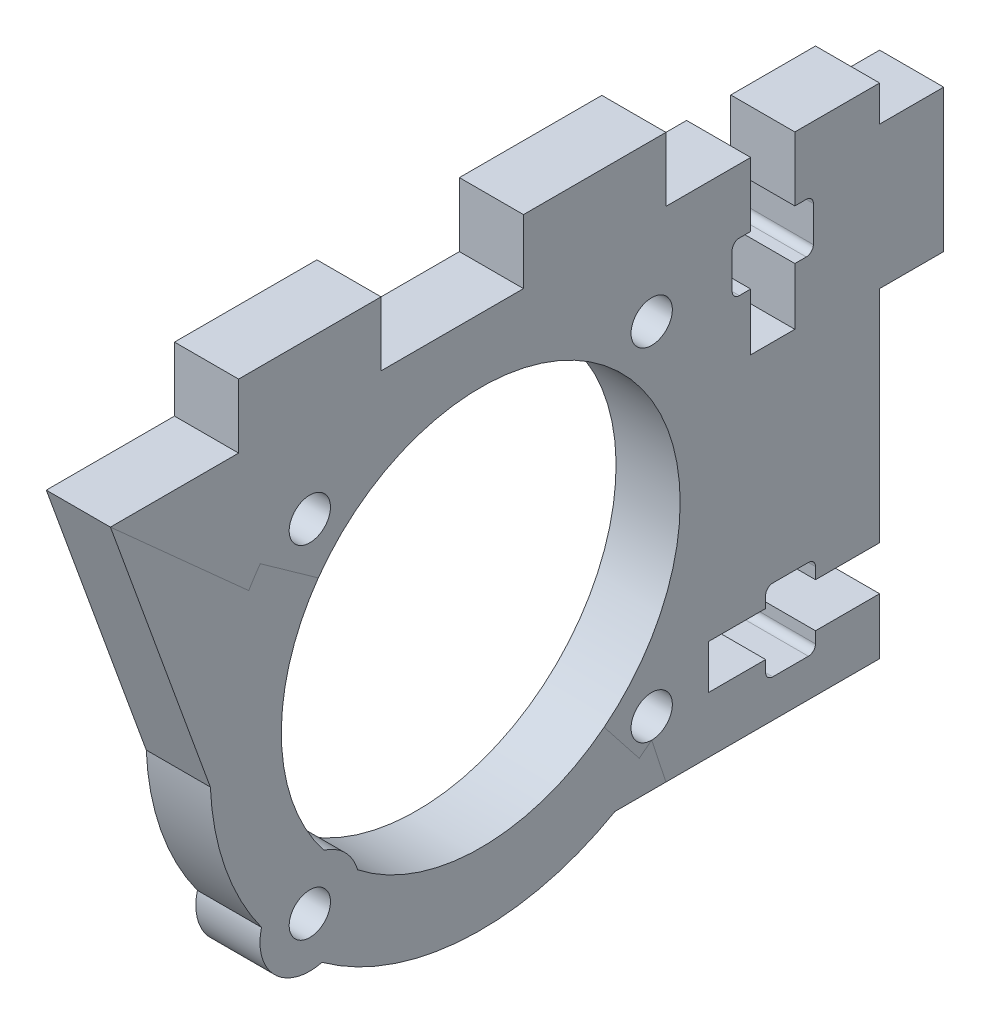
SolidWorks part; units mm, degrees
ref_plane "Front Plane" through (0, 0, 0) normal (0, 0, 1) x (1, 0, 0)
ref_plane "Top Plane" through (0, 0, 0) normal (0, 1, 0) x (1, 0, 0)
ref_plane "Right Plane" through (0, 0, 0) normal (1, 0, 0) x (0, 0, -1)
sketch "Sketch1" plane through (0, 0, 0) normal (1, 0, 0) x (0, 0, -1)
  line L0 (0, 0) -> (0, -35)
  line L1 (0, -35) -> (-54, 0)
  line L2 (-54, 0) -> (0, 0)
  dimension "D1" = 35
  dimension "D2" = 54
extrude "Boss-Extrude1" add sketch "Sketch1" along normal blind 4.5
sketch "Sketch2" plane through (4.5, 0, 0) normal (1, 0, 0) x (0, 0, -1)
  line L0 (0, -35) -> (0, 0) construction
  line L1 (-4.5, -2.5) -> (4.5, -2.5)
  line L2 (-4.5, -2.5) -> (-4.5, -12.5)
  line L3 (-4.5, -12.5) -> (4.5, -12.5)
  line L4 (4.5, -2.5) -> (4.5, -12.5)
  line L5 (-4.5, -2.5) -> (4.5, -12.5) construction
  line L6 (-4.5, -12.5) -> (4.5, -2.5) construction
  line L7 (0, 0) -> (-54, 0) construction
  point P0 (0, -7.5)
  dimension "D1" = 10
  dimension "D2" = 7.5
  dimension "D3" = 4.5
extrude "Boss-Extrude2" add sketch "Sketch2" against normal through all
sketch "Sketch3" plane through (4.5, 0, 0) normal (1, 0, 0) x (0, 0, -1)
  line L0 (0, -35) -> (-15, -35)
  line L1 (0, -25) -> (-54, 0)
  line L4 (0, -35) -> (0, -12.5) construction
  line L5 (0, -25) -> (0, -35)
  line L6 (-54, 0) -> (-15, -35)
  dimension "D1" = 15
  dimension "D2" = 10
extrude "Boss-Extrude3" add sketch "Sketch3" against normal through all
sketch "Sketch4" plane through (4.5, 0, 0) normal (1, 0, 0) x (0, 0, -1)
  line L0 (0, -29.5) -> (-12, -29.5) construction
  line L1 (0, -35) -> (0, -12.5) construction
  line L2 (0, -27.95) -> (-12, -27.95) construction
  line L3 (-12, -27.95) -> (-12, -31.05) construction
  line L4 (0, -31.05) -> (0, -27.95)
  line L5 (0, -27.95) -> (-4.5, -27.95)
  line L6 (-4.5, -27.95) -> (-4.5, -27.15)
  line L7 (-5, -26.65) -> (-7.5, -26.65)
  line L8 (-8, -27.15) -> (-8, -27.95)
  line L9 (-8, -27.95) -> (-12, -27.95)
  line L10 (-12, -27.95) -> (-12, -31.05)
  line L12 (0, -31.05) -> (-12, -31.05) construction
  line L13 (-8, -31.05) -> (-12, -31.05)
  line L14 (-8, -31.85) -> (-8, -31.05)
  line L15 (-5, -32.35) -> (-7.5, -32.35)
  line L16 (-4.5, -31.05) -> (-4.5, -31.85)
  line L17 (0, -31.05) -> (-4.5, -31.05)
  line L18 (4.5, -12.5) -> (4.5, -2.5) construction
  line L19 (0, -18.5) -> (-33.3857, -18.5) construction
  line L20 (-54, 0) -> (-15, -35) construction
  line L37 (0, -31.05) -> (-12, -31.05) construction
  arc A0 (-8, -31.85) -> (-7.5, -32.35) centre (-7.5, -31.85) ccw
  arc A1 (-5, -32.35) -> (-4.5, -31.85) centre (-5, -31.85) ccw
  arc A2 (-4.5, -27.15) -> (-5, -26.65) centre (-5, -27.15) ccw
  arc A3 (-7.5, -26.65) -> (-8, -27.15) centre (-7.5, -27.15) ccw
  point P10 (4.5, -7.5)
  point P20 (-8, -32.35)
  point P23 (-4.5, -32.35)
  point P26 (-4.5, -26.65)
  point P29 (-8, -26.65)
  dimension "D7" = 0.5
  dimension "D1" = 12
  dimension "D2" = 1.55
  dimension "D3" = 2.85
  dimension "D4" = 3.5
  dimension "D5" = 8
  dimension "D6" = 22
extrude "Cut-Extrude1" cut sketch "Sketch4" against normal through all
sketch "Sketch5" plane through (4.5, 0, 0) normal (1, 0, 0) x (0, 0, -1)
  line L0 (0, 0) -> (-54, 0) construction
  line L1 (-25, 4.5) -> (-15, 4.5)
  line L2 (-25, 4.5) -> (-25, 0)
  line L3 (0, 0) -> (-54, 0) construction
  line L4 (-15, 4.5) -> (-15, 0)
  line L5 (-25, 4.5) -> (-20, 0) construction
  line L6 (-20, 0) -> (-15, 4.5) construction
  line L7 (-30, 0) -> (-30, 4.5) construction
  line L8 (-40, 0) -> (-45, 4.5) construction
  line L9 (-35, 4.5) -> (-40, 0) construction
  line L10 (-45, 4.5) -> (-45, 0)
  line L12 (-35, 4.5) -> (-35, 0)
  line L13 (-35, 4.5) -> (-45, 4.5)
  line L14 (-20, 0) -> (-15, 4.5) construction
  line L15 (-15, 0) -> (-25, 0)
  line L16 (-35, 0) -> (-45, 0)
  point P0 (-20, 0)
  point P14 (-40, 0)
  dimension "D3" = 4.5
  dimension "D1" = 20
  dimension "D2" = 10
  dimension "D4" = 20
  dimension "D5" = 5
extrude "Boss-Extrude4" add sketch "Sketch5" against normal through all
sketch "Sketch8" [suppressed] plane through (4.5, 0, 0) normal (1, 0, 0) x (0, 0, -1)
  line L0 (-15, -30) -> (-27, -30) construction
  line L1 (-15, -35) -> (-27, -35)
  line L2 (-15, -25) -> (-27, -25)
  line L3 (-15, -35) -> (0, -35) construction
  line L4 (-15, -25) -> (-15, -35)
  arc A1 (-27, -25) -> (-27, -35) centre (-27, -30) ccw
  dimension "D5" = 5
  dimension "D1" = 0
  dimension "D2" = 12
  dimension "D3" = 0
  dimension "D4" = 10
extrude "Boss-Extrude5" [suppressed] add sketch "Sketch8" against normal up to surface (4.5 mm away)
sketch "Sketch9" [suppressed] plane through (4.5, 0, 0) normal (1, 0, 0) x (0, 0, -1)
  line L0 (-27, -30) -> (-22, -30) construction
  line L1 (-27, -27) -> (-22, -27)
  line L2 (-27, -33) -> (-22, -33)
  arc A0 (-27, -27) -> (-27, -33) centre (-27, -30) ccw
  arc A1 (-22, -33) -> (-22, -27) centre (-22, -30) ccw
  point P3 (-24.5, -30)
  dimension "D1" = 3
  dimension "D2" = 5
extrude "Cut-Extrude3" [suppressed] cut sketch "Sketch9" against normal through all
sketch "Sketch10" plane through (0, 0, 0) normal (-1, 0, 0) x (0, 0, 1)
  line L0 (15, -35) -> (54, -12)
  line L1 (54, -12) -> (54, 0)
  line L3 (54, 0) -> (15, -35)
  dimension "D1" = 12
extrude "Boss-Extrude6" [suppressed] add sketch "Sketch10" against normal through all
sketch "Sketch6" plane through (4.5, 0, 0) normal (1, 0, 0) x (0, 0, -1)
  line L0 (-30, 0) -> (-30, -11) construction
  line L1 (-25, 0) -> (-35, 0) construction
  line L2 (-28.45, -11) -> (-31.55, -11) construction
  line L3 (-31.55, -11) -> (-31.55, 0) construction
  line L4 (-28.45, 0) -> (-31.55, 0)
  line L5 (-31.55, 0) -> (-31.55, -4.5)
  line L6 (-31.55, -4.5) -> (-32.35, -4.5)
  line L7 (-32.85, -5) -> (-32.85, -7.5)
  line L8 (-32.35, -8) -> (-31.55, -8)
  line L9 (-31.55, -8) -> (-31.55, -11)
  line L10 (-31.55, -11) -> (-28.45, -11)
  line L11 (-28.45, -11) -> (-28.45, 0) construction
  line L12 (-28.45, -8) -> (-28.45, -11)
  line L13 (-27.65, -8) -> (-28.45, -8)
  line L14 (-27.15, -5) -> (-27.15, -7.5)
  line L15 (-28.45, -4.5) -> (-27.65, -4.5)
  line L16 (-28.45, 0) -> (-28.45, -4.5)
  arc A0 (-32.85, -7.5) -> (-32.35, -8) centre (-32.35, -7.5) ccw
  arc A1 (-32.35, -4.5) -> (-32.85, -5) centre (-32.35, -5) ccw
  arc A2 (-27.65, -4.5) -> (-27.15, -5) centre (-27.65, -5) cw
  arc A3 (-27.15, -7.5) -> (-27.65, -8) centre (-27.65, -7.5) cw
  point P12 (-32.85, -8)
  point P15 (-32.85, -4.5)
  point P26 (-27.15, -4.5)
  point P27 (-27.15, -8)
  dimension "D2" = 1.55
  dimension "D4" = 3.5
  dimension "D6" = 0.5
  dimension "D1" = 11
  dimension "D3" = 8
  dimension "D5" = 2.85
extrude "Cut-Extrude2" [suppressed] cut sketch "Sketch6" against normal through all
sketch "Sketch11" plane through (0, 0, 0) normal (-1, 0, 0) x (0, 0, 1)
  line L0 (7.5, 0) -> (7.5, -12) construction
  line L1 (0, 0) -> (15, 0) construction
  line L2 (5.95, -12) -> (9.05, -12)
  line L3 (9.05, -12) -> (9.05, -8)
  line L4 (9.05, -8) -> (9.85, -8)
  line L5 (10.35, -7.5) -> (10.35, -5)
  line L6 (9.85, -4.5) -> (9.05, -4.5)
  line L7 (9.05, -4.5) -> (9.05, 0)
  line L8 (9.05, 0) -> (5.95, 0)
  line L9 (9.05, -8) -> (9.05, -4.5) construction
  line L10 (0, 0) -> (15, 0) construction
  line L11 (5.95, -8) -> (5.95, -4.5) construction
  line L12 (5.95, -4.5) -> (5.95, 0)
  line L13 (5.15, -4.5) -> (5.95, -4.5)
  line L14 (4.65, -7.5) -> (4.65, -5)
  line L15 (5.95, -8) -> (5.15, -8)
  line L16 (5.95, -12) -> (5.95, -8)
  arc A0 (10.35, -5) -> (9.85, -4.5) centre (9.85, -5) ccw
  arc A1 (5.15, -4.5) -> (4.65, -5) centre (5.15, -5) ccw
  arc A2 (9.85, -8) -> (10.35, -7.5) centre (9.85, -7.5) ccw
  arc A3 (4.65, -7.5) -> (5.15, -8) centre (5.15, -7.5) ccw
  point P11 (7.5, 0)
  point P22 (10.35, -4.5)
  point P25 (4.65, -4.5)
  point P28 (10.35, -8)
  point P31 (4.65, -8)
  dimension "D7" = 0.5
  dimension "D1" = 12
  dimension "D3" = 2.85
  dimension "D8" = 0.5
  dimension "D2" = 3.5
  dimension "D4" = 8
  dimension "D5" = 1.55
  dimension "D6" = 0
extrude "Cut-Extrude4" cut sketch "Sketch11" against normal through all
sketch "Sketch12" plane through (0, 0, 0) normal (-1, 0, 0) x (0, 0, 1)
  line L0 (28, -18.5) -> (16, -6.5) construction
  line L1 (28, -18.5) -> (28, -4.5) construction
  line L2 (28, -18.5) -> (40, -6.5) construction
  line L3 (28, -18.5) -> (14, -18.5) construction
  line L4 (28, -18.5) -> (16, -30.5) construction
  line L5 (28, -18.5) -> (16, -6.5) construction
  line L6 (0, -27.95) -> (0, -12.5) construction
  line L7 (25, 0) -> (35, 0) construction
  circle A0 centre (28, -18.5) radius 14
  circle A1 centre (16, -6.5) radius 1.45
  circle A2 centre (40, -6.5) radius 1.45
  circle A3 centre (16, -30.5) radius 1.45
  dimension "D1" = 28
  dimension "D2" = 2.9
  dimension "D3" = 12
  dimension "D4" = 45
  dimension "D5" = 28
  dimension "D6" = 18.5
extrude "FanCutout" cut sketch "Sketch12" against normal through all
sketch "Sketch13" plane through (0, 0, 0) normal (-1, 0, 0) x (0, 0, 1)
  line L0 (39.4071, -10.3834) -> (43.481, -7.4847)
  line L1 (19.3358, -29.4969) -> (16.2414, -33.4243)
  line L6 (28, -18.5) -> (54, 0) construction
  line L7 (28, -18.5) -> (15, -35) construction
  arc A0 (19.3358, -29.4969) -> (39.4071, -10.3834) centre (28, -18.5) ccw
  arc A1 (16.2414, -33.4243) -> (43.481, -7.4847) centre (28, -18.5) ccw
  arc A3 (40.4722, -12.1404) -> (20.333, -30.214) centre (28, -18.5) ccw construction
  dimension "D1" = 5
extrude "Boss-Extrude7" add sketch "Sketch13" against normal through all
sketch "Sketch14" plane through (0, 0, 0) normal (-1, 0, 0) x (0, 0, 1)
  line L0 (28, -4.5) -> (28, -32.5) construction
  line L1 (28, -18.5) -> (40, -30.5) construction
  circle A0 centre (28, -18.5) radius 14 construction
  circle A1 centre (40, -30.5) radius 3.5
  dimension "D2" = 7
  dimension "D1" = 45
  dimension "D3" = 12
extrude "Boss-Extrude8" add sketch "Sketch14" against normal through all
sketch "Sketch15" plane through (0, 0, 0) normal (-1, 0, 0) x (0, 0, 1)
  line L0 (42.4749, -32.9749) -> (28, -18.5) construction
  arc A0 (39.1388, -33.8924) -> (43.3924, -29.6388) centre (40, -30.5) ccw construction
  circle A1 centre (40, -30.5) radius 1.45
  dimension "D1" = 2.9
extrude "Cut-Extrude6" cut sketch "Sketch15" against normal through all
sketch "Sketch16" [suppressed] plane through (4.5, 0, 0) normal (1, 0, 0) x (0, 0, -1)
  line L0 (0, -34.5) -> (-39, -34.5) construction
  line L1 (0, -27.95) -> (0, -12.5) construction
  line L2 (-15, -34.5) -> (-39, -34.5) construction
  line L3 (-15, -38.5) -> (-39, -38.5)
  line L4 (-15, -30.5) -> (-39, -30.5)
  arc A0 (-15, -38.5) -> (-15, -30.5) centre (-15, -34.5) ccw
  arc A1 (-39, -30.5) -> (-39, -38.5) centre (-39, -34.5) ccw
  point P5 (-27, -34.5)
  point P12 (0, -20.225)
  dimension "D1" = 4
  dimension "D2" = 34.5
  dimension "D3" = 39
  dimension "D4" = 15
extrude "Boss-Extrude9" [suppressed] add sketch "Sketch16" against normal through all
sketch "Sketch17" [suppressed] plane through (4.5, 0, 0) normal (1, 0, 0) x (0, 0, -1)
  line L0 (-43, -34.5) -> (0, -34.5) construction
  line L1 (0, -27.75) -> (0, -12.5) construction
  line L2 (-26.5, -34.5) -> (-26.5, -20.0064) construction
  arc A0 (-42.1823, -32.0766) -> (-39, -38.5) centre (-39, -34.5) ccw construction
  circle A1 centre (-39, -34.5) radius 1.55
  circle A2 centre (-14, -34.5) radius 1.55
  dimension "D1" = 2.9
  dimension "D2" = 12.5
extrude "Cut-Extrude7" [suppressed] cut sketch "Sketch17" against normal through all
sketch "Sketch18" [suppressed] plane through (4.5, 0, 0) normal (1, 0, 0) x (0, 0, -1)
  line L0 (-15, -38.5) -> (0, -35)
  line L1 (0, -35) -> (-11.0314, -35)
  line L2 (-11.0314, -35) -> (-15, -38.5)
extrude "Boss-Extrude10" [suppressed] add sketch "Sketch18" against normal through all
sketch "Sketch20" [suppressed] plane through (4.5, 0, 0) normal (1, 0, 0) x (0, 0, -1)
  line L0 (0, -35) -> (0, -31.05) construction
  line L1 (-9, -38) -> (-37.9081, -38)
  line L2 (-40.7232, -36.0371) -> (-54, 0)
  line L3 (-54, 0) -> (-15, -35)
  line L4 (-15, -35) -> (-6, -35)
  line L5 (-9, -38) -> (-6, -35)
  line L6 (-40.7232, -36.0371) -> (-40, -38) construction
  line L7 (-40, -38) -> (-37.9081, -38) construction
  arc A1 (-37.9081, -38) -> (-40.7232, -36.0371) centre (-37.9081, -35) cw
  point P0 (0, -33.025)
  point P14 (-40, -38)
  dimension "D3" = 6
  dimension "D4" = 3
  dimension "D1" = 40
  dimension "D2" = 3
  dimension "D5" = 135
extrude "Boss-Extrude11" [suppressed] add sketch "Sketch20" against normal through all
sketch "Sketch21" [suppressed] plane through (4.5, 0, 0) normal (1, 0, 0) x (0, 0, -1)
  line L0 (0, -34.5) -> (-41.2895, -34.5) construction
  line L1 (0, -35) -> (0, -31.05) construction
  line L2 (-54, 0) -> (-40.7232, -36.0371) construction
  line L3 (0, -27.95) -> (0, -12.5) construction
  circle A0 centre (-36, -34.5) radius 1.45
  circle A1 centre (-11, -34.5) radius 1.45
  dimension "D2" = 2.9
  dimension "D3" = 2.9
  dimension "D1" = 25
  dimension "D4" = 34.5
  dimension "D5" = 11
extrude "Cut-Extrude8" [suppressed] cut sketch "Sketch21" against normal through all
sketch "Sketch22" [suppressed] plane through (4.5, 0, 0) normal (1, 0, 0) x (0, 0, -1)
  line L0 (0, -27.95) -> (0, -12.5) construction
  line L1 (-25, 0) -> (-35, 0) construction
  circle A0 centre (-28, -18) radius 13.25
  dimension "D2" = 18
  dimension "D3" = 26.5
  dimension "D1" = 28
extrude "Cut-Extrude9" [suppressed] cut sketch "Sketch22" against normal through all
sketch "Sketch24" plane through (0, 0, 0) normal (-1, 0, 0) x (0, 0, 1)
  line L0 (15, -35) -> (20, -35)
  line L1 (20, -35) -> (16, -31.95)
  line L2 (16, -31.95) -> (15, -35)
  circle A0 centre (16, -30.5) radius 1.45 construction
  dimension "D1" = 5
extrude "Boss-Extrude13" add sketch "Sketch24" against normal through all
sketch "Sketch25" plane through (0, 0, 0) normal (-1, 0, 0) x (0, 0, 1)
  line L0 (54, 0) -> (46.9826, -19.3121)
  line L1 (46.9826, -19.3121) -> (44.2874, -8.7164)
  line L2 (44.2874, -8.7164) -> (54, 0)
  arc A0 (43.3924, -29.6388) -> (44.2874, -8.7164) centre (28, -18.5) ccw construction
extrude "Boss-Extrude15" add sketch "Sketch25" against normal through all
equation "\"X-ROD-SPACING\"=45"
equation "\"Y-ROD-SPACING\"=75"
equation "\"Z-ROD-SPACING\"=17.5"
equation "\"Y-BED-OFFSET\"=2"
equation "\"Y-BED-ROD-INSET\"=3.5"
equation "\"Y-BED-SCREW-SPACING\"=209"
equation "\"Y-BED-SCREW-CUTOUT-SLOT-HEIGHT\"=2.5"
equation "\"T-SLOT-NUT-FILLET-RADIUS\"=0.5"
equation "\"T-SLOT-SCREW-SHAFT-RADIUS\"=1.55"
equation "\"T-SLOT-SCREW-SHAFT-CUTOUT-LENGTH\"=11"
equation "\"T-SLOT-NUT-DEPTH\"=3.5"
equation "\"T-SLOT-NUT-WIDTH\"=2.85"
equation "\"T-SLOT-NUT-END-DISTANCE\"=8"
equation "\"ACRYLIC-THICKNESS\"=10"
equation "\"ACRYLIC-THICKNESS2\"=4.5"
equation "\"ACRYLIC-TAB-CUTOUT-SIZE\"=\"ACRYLIC-THICKNESS\"+\"ACRYLIC-TAB-TOLERANCE\"*2"
equation "\"ACRYLIC-TAB-WIDTH\"=\"ACRYLIC-THICKNESS\""
equation "\"ACRYLIC-M3-HOLE\"=2.9"
equation "\"SMOOTHROD-CAP-SCREW-DISTANCE\"=20"
equation "\"FRAME-WIDTH-INNER\"=370"
equation "\"NEMA17-HOLE-SPACING\"=31"
equation "\"NEMA17-CENTRAL-CUTOUT\"=22.5"
equation "\"Z-BRACKET-REACH\"=57"
equation "\"Z-ROD-INSET\"=13.5"
equation "\"TOP-BRACKET-SPACING\"=40"
equation "\"SMOOTHROD-X-LENGTH\"=350"
equation "\"SMOOTHROD-Y-LENGTH\"=350"
equation "\"SMOOTHROD-Z-LENGTH\"=350"
equation "\"SMOOTHROD-TIGHTENING-HEADROOM\"=.25"
equation "\"LEADSCREW-Z-LENGTH\"=300"
equation "\"SCREW-LENGTH-FRAME\"=\"ACRYLIC-THICKNESS\" + 10"
equation "\"SCREW-LENGTH-MOTOR\"=\"ACRYLIC-THICKNESS\" + 5"
equation "\"SCREW-LENGTH-EXTRUDER\"=28"
equation "\"SCREW-HEAD-RADIUS\"=6"
equation "\"PRINTED-X-SMOOTHROD-DIAMETER\"=8.8"
equation "\"PRINTED-X-SMOOTHROD-CUTOUT\"=10"
equation "\"PRINTED-X-BASE-HEIGHT\"=10"
equation "\"PRINTED-LM8UU-CUTOUT-SIZE\"=15.5"
equation "\"PRINTED-LM8UU-CUTOUT-LENGTH\"=24.5"
equation "\"PRINTED-X-IDLER-HEIGHT\"=16"
equation "\"PSU-MOUNTING-WIDTH\"=95"
equation "\"PSU-MOUNTING-HEIGHT\"=177"
equation "\"Y-BELT-TO-ROD-DISTANCE\"=20"
equation "\"SPOOL-HOLDER-ROD-SPACING\"=150"
equation "\"ACRYLIC-X-CARRIAGE-WIDTH\"=55"
equation "\"ACRYLIC-X-CARRIAGE-HEIGHT\"=75"
equation "\"ACRYLIC-X-CARRIAGE-SCREW-SPACING-X\"=15"
equation "\"ACRYLIC-X-CARRIAGE-SCREW-SPACING-Y\"=33"
equation "\"ACRYLIC-X-CARRIAGE-CENTER-TAB-SPACING\"=14"
equation "\"ACRYLIC-X-CARRIAGE-EXTRUDER-SHELF-DEPTH\"=\"ACRYLIC-X-CARRIAGE-EXTRUDER-OFFSET\" + 28"
equation "\"D2@Sketch1\"=\"ACRYLIC-X-CARRIAGE-EXTRUDER-SHELF-DEPTH\""
equation "\"D1@Boss-Extrude1\"=\"ACRYLIC-THICKNESS2\""
equation "\"D1@Sketch2\"=\"ACRYLIC-TAB-WIDTH\""
equation "\"D3@Sketch2\"=\"ACRYLIC-THICKNESS2\""
equation "\"ACRYLIC-X-CARRIAGE-LM8UU-CUTOUT-WIDTH\"=24.25"
equation "\"ACRYLIC-X-CARRIAGE-EXTRUDER-BRACE-SPACING\"=23"
equation "\"ACRYLIC-X-CARRIAGE-EXTRUDER-BRACE-HEIGHT\"=35"
equation "\"D1@Sketch1\"=\"ACRYLIC-X-CARRIAGE-EXTRUDER-BRACE-HEIGHT\""
equation "\"D1@Sketch4\"=\"T-SLOT-SCREW-SHAFT-CUTOUT-LENGTH\"+1"
equation "\"D2@Sketch4\"=\"T-SLOT-SCREW-SHAFT-RADIUS\""
equation "\"D3@Sketch4\"=\"T-SLOT-NUT-WIDTH\""
equation "\"D4@Sketch4\"=\"T-SLOT-NUT-DEPTH\""
equation "\"D5@Sketch4\"=\"T-SLOT-NUT-END-DISTANCE\""
equation "\"D7@Sketch4\"=\"T-SLOT-NUT-FILLET-RADIUS\""
equation "\"ACRYLIC-X-CARRIAGE-EXTRUDER-BRACE-SCREW-SPACING\"=22"
equation "\"D6@Sketch4\"=\"ACRYLIC-X-CARRIAGE-EXTRUDER-BRACE-SCREW-SPACING\""
equation "\"ACRYLIC-X-CARRIAGE-EXTRUDER-BRACE-TAB-OFFSET\"=20"
equation "\"D1@Sketch5\"=\"ACRYLIC-X-CARRIAGE-EXTRUDER-BRACE-TAB-OFFSET\""
equation "\"D2@Sketch5\"=\"ACRYLIC-TAB-WIDTH\""
equation "\"D3@Sketch5\"=\"ACRYLIC-THICKNESS2\""
equation "\"ACRYLIC-X-CARRIAGE-EXTRUDER-OFFSET\"=26"
equation "\"ACRYLIC-X-CARRIAGE-EXTRUDER-ANGLE\"=90"
equation "\"D1@Sketch6\"=\"T-SLOT-SCREW-SHAFT-CUTOUT-LENGTH\""
equation "\"D2@Sketch6\"=\"T-SLOT-SCREW-SHAFT-RADIUS\""
equation "\"D3@Sketch6\"=\"T-SLOT-NUT-END-DISTANCE\""
equation "\"D4@Sketch6\"=\"T-SLOT-NUT-DEPTH\""
equation "\"D5@Sketch6\"=\"T-SLOT-NUT-WIDTH\""
equation "\"D6@Sketch6\"=\"T-SLOT-NUT-FILLET-RADIUS\""
equation "\"D1@Sketch11\"=\"T-SLOT-SCREW-SHAFT-CUTOUT-LENGTH\"+1"
equation "\"D2@Sketch11\"=\"T-SLOT-NUT-DEPTH\""
equation "\"D3@Sketch11\"=\"T-SLOT-NUT-WIDTH\""
equation "\"D4@Sketch11\"=\"T-SLOT-NUT-END-DISTANCE\""
equation "\"D5@Sketch11\"=\"T-SLOT-SCREW-SHAFT-RADIUS\""
equation "\"D7@Sketch11\"=\"T-SLOT-NUT-FILLET-RADIUS\""
equation "\"D8@Sketch11\"=\"T-SLOT-NUT-FILLET-RADIUS\""
equation "\"D2@Sketch12\"=\"ACRYLIC-M3-HOLE\""
equation "\"D1@Sketch15\"=\"ACRYLIC-M3-HOLE\""
equation "\"D1@Sketch17\"=\"ACRYLIC-M3-HOLE\""
equation "\"D2@Sketch21\"=\"ACRYLIC-M3-HOLE\""
equation "\"D3@Sketch21\"=\"ACRYLIC-M3-HOLE\""
